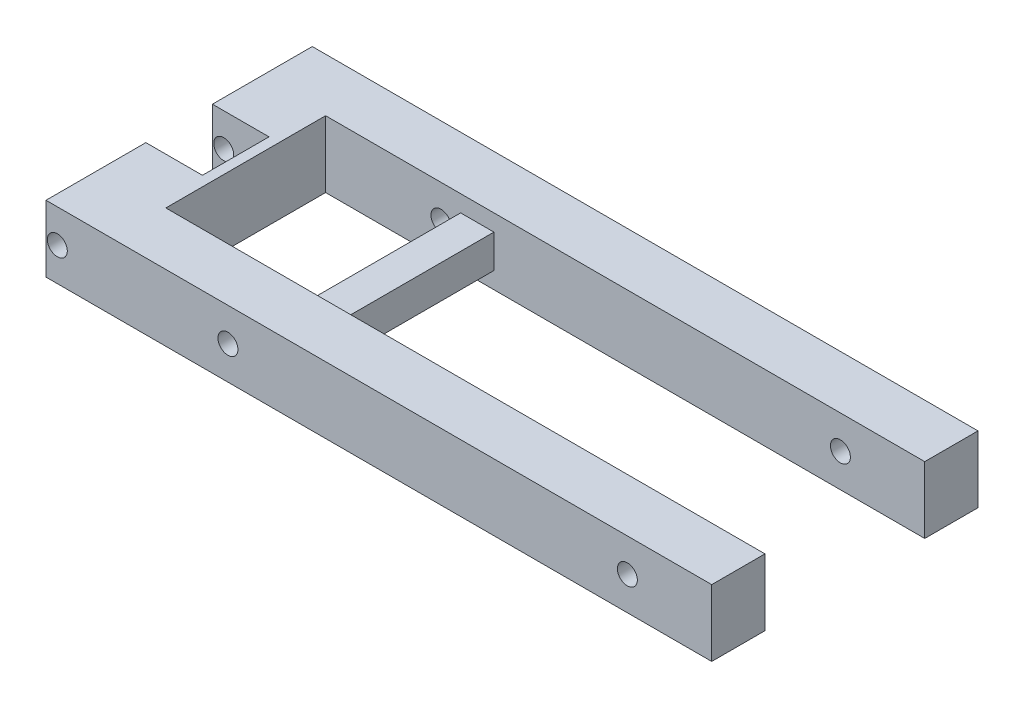
SolidWorks part; units mm, degrees
ref_plane "Piano frontale" through (0, 0, 0) normal (0, 0, 1) x (1, 0, 0)
ref_plane "Piano superiore" through (0, 0, 0) normal (0, 1, 0) x (1, 0, 0)
ref_plane "Piano destro" through (0, 0, 0) normal (1, 0, 0) x (0, 0, -1)
sketch "Schizzo1" plane through (0, 0, 0) normal (0, 1, 0) x (1, 0, 0)
  line L0 (0, 0) -> (-410.3417, 0) construction
  line L1 (0, 0) -> (510.4978, 0) construction
  line L5 (-332.8468, -200) -> (-332.8468, 200)
  line L7 (-332.8468, 200) -> (667.1532, 200)
  line L8 (667.1532, 200) -> (667.1532, 120)
  line L9 (667.1532, 120) -> (-232.8468, 120)
  line L10 (-232.8468, 120) -> (-232.8468, -120)
  line L11 (667.1532, -120) -> (-232.8468, -120)
  line L12 (667.1532, -200) -> (667.1532, -120)
  line L13 (-332.8468, -200) -> (667.1532, -200)
  point P11 (-232.8468, 0)
  point P14 (-332.8468, 0)
  dimension "D1" = 1000
  dimension "D2" = 100
  dimension "D4" = 232.8468
  dimension "D3" = 80
  dimension "D5" = 120
extrude "Estrusione-Estrusione1" add sketch "Schizzo1" along normal blind 100
sketch "Schizzo2" plane through (0, 0, 0) normal (0, 0, 1) x (1, 0, 0)
  line L0 (-332.8468, 50) -> (667.1532, 50) construction
  line L8 (-332.8468, 100) -> (-332.8468, 0) construction
  line L13 (667.1532, 100) -> (667.1532, 0) construction
  circle A7 centre (-315.8468, 50) radius 15
  circle A8 centre (-59.5468, 50) radius 15
  circle A9 centre (540.4532, 50) radius 15
  dimension "D1" = 30
  dimension "D2" = 30
  dimension "D3" = 30
  dimension "D4" = 256.3
  dimension "D5" = 600
  dimension "D6" = 17
extrude "Taglio-Estrusione5" cut sketch "Schizzo2" against normal through all both and the other way through all
sketch "Schizzo3" plane through (0, 0, 0) normal (0, 1, 0) x (1, 0, 0)
  line L0 (-14.9222, 0) -> (-32.6568, 0) construction
  line L1 (-332.8468, -50) -> (-332.8468, 50)
  line L2 (-332.8468, 50) -> (-247.8468, 50)
  line L3 (-247.8468, 50) -> (-247.8468, -50)
  line L4 (667.1532, -120) -> (-232.8468, -120)
  line L5 (667.1532, -120) -> (-232.8468, -120)
  line L6 (-232.8468, -120) -> (-232.8468, 120)
  line L7 (-232.8468, -120) -> (-232.8468, 120)
  line L13 (-332.8468, -50) -> (-247.8468, -50)
  line L21 (-232.8468, 120) -> (667.1532, 120)
  line L22 (-232.8468, 120) -> (667.1532, 120)
  line L23 (667.1532, 120) -> (667.1532, 200)
  line L24 (667.1532, 120) -> (667.1532, 200)
  line L25 (667.1532, 200) -> (-332.8468, 200)
  line L26 (667.1532, 200) -> (-332.8468, 200)
  line L27 (-332.8468, 200) -> (-332.8468, -200)
  line L28 (-332.8468, 200) -> (-332.8468, -200)
  line L29 (-332.8468, -200) -> (667.1532, -200)
  line L30 (-332.8468, -200) -> (667.1532, -200)
  line L31 (667.1532, -200) -> (667.1532, -120)
  line L32 (667.1532, -200) -> (667.1532, -120)
  point P21 (-247.8468, 0)
  point P22 (-332.8468, 0)
  dimension "D2" = 85
  dimension "D3" = 0
  dimension "D4" = 50
  dimension "D1" = 0
extrude "Taglio-Estrusione6" cut sketch "Schizzo3" along normal through all both contours L3 L13 L1 L2
sketch "Schizzo4" plane through (0, 0, 0) normal (0, 0, 1) x (1, 0, 0)
  line L0 (-30, 75) -> (20, 75)
  line L1 (20, 75) -> (20, 25)
  line L2 (20, 25) -> (-30, 25)
  line L3 (-30, 25) -> (-30, 75)
  line L4 (-332.8468, 0) -> (667.1532, 0) construction
  line L5 (-332.8468, 100) -> (667.1532, 100) construction
  dimension "D1" = 25
  dimension "D2" = 25
  dimension "D3" = 20
  dimension "D4" = 50
extrude "Estrusione-Estrusione2" add sketch "Schizzo4" along normal up to next and the other way up to next
